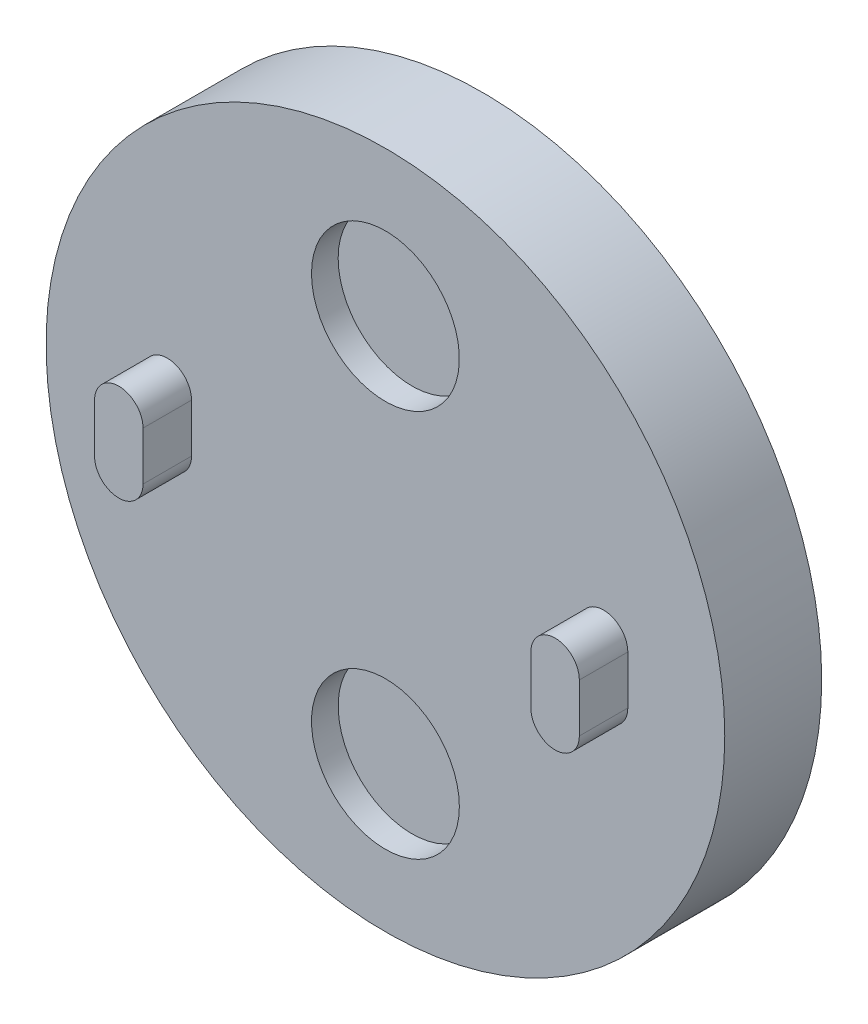
SolidWorks part; units mm, degrees
material "ABS"
ref_plane "Front Plane" through (0, 0, 0) normal (0, 0, 1) x (1, 0, 0)
ref_plane "Top Plane" through (0, 0, 0) normal (0, 1, 0) x (1, 0, 0)
ref_plane "Right Plane" through (0, 0, 0) normal (1, 0, 0) x (0, 0, -1)
sketch "Sketch3" plane through (0, 0, -51.6128) normal (0, 0, 1) x (1, 0, 0)
  circle A0 centre (0, 8) radius 14
  dimension "D1" = 28
extrude "Boss-Extrude1" add sketch "Sketch3" against normal blind 3 and the other way blind 1
sketch "Sketch6" plane through (0, 0, -50.6128) normal (0, 0, 1) x (1, 0, 0)
  line L0 (-14, 8) -> (14, 8) construction
  circle A0 centre (0, 0) radius 3.05
  circle A1 centre (0, 8) radius 14 construction
  circle A2 centre (0, 16) radius 3.05
  dimension "D1" = 6.1
extrude "Cut-Extrude2" cut sketch "Sketch6" against normal blind 1.1
sketch "Sketch7" plane through (0, 0, -50.6128) normal (0, 0, 1) x (1, 0, 0)
  line L0 (-14, 8) -> (14, 8) construction
  line L1 (-9, 9) -> (-9, 7) construction
  line L2 (-8, 9) -> (-8, 7)
  line L3 (-10, 9) -> (-10, 7)
  line L4 (0, -6) -> (0, 22) construction
  line L5 (9, 9) -> (9, 7) construction
  line L6 (8, 9) -> (8, 7)
  line L7 (10, 9) -> (10, 7)
  circle A0 centre (0, 8) radius 14 construction
  arc A1 (-8, 9) -> (-10, 9) centre (-9, 9) ccw
  arc A2 (-10, 7) -> (-8, 7) centre (-9, 7) ccw
  arc A3 (8, 9) -> (10, 9) centre (9, 9) cw
  arc A4 (10, 7) -> (8, 7) centre (9, 7) cw
  point P7 (-9, 8)
  point P16 (9, 8)
  dimension "D1" = 2
  dimension "D2" = 2
  dimension "D3" = 5
extrude "Boss-Extrude2" add sketch "Sketch7" along normal blind 2
sketch "Sketch8" plane through (0, 0, -54.6128) normal (0, 0, -1) x (-1, 0, 0)
  line L0 (-1.55, 10.0248) -> (-1.55, 5.9752)
  line L1 (0, 10.55) -> (0, 5.45) construction
  line L5 (1.55, 10.0248) -> (1.55, 5.9752)
  arc A0 (-1.55, 5.9752) -> (1.55, 5.9752) centre (0, 8) ccw construction
  arc A1 (-1.55, 5.9752) -> (1.55, 5.9752) centre (0, 8) ccw
  arc A2 (1.55, 10.0248) -> (-1.55, 10.0248) centre (0, 8) ccw construction
  arc A3 (1.55, 10.0248) -> (-1.55, 10.0248) centre (0, 8) ccw
  dimension "D1" = 5.1
  dimension "D2" = 3.1
extrude "Cut-Extrude3" cut sketch "Sketch8" against normal blind 3
